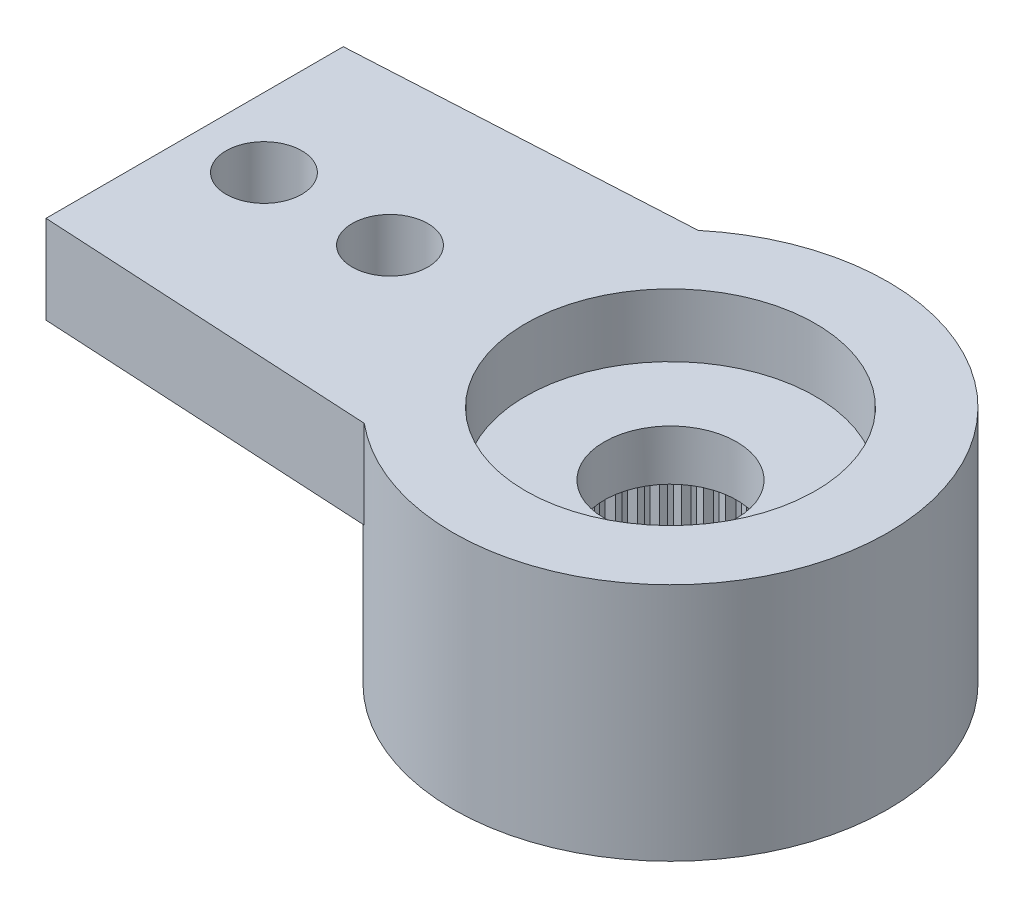
SolidWorks part; units mm, degrees
material "PVC Rígido"
ref_plane "Plano frontal" through (0, 0, 0) normal (0, 0, 1) x (1, 0, 0)
ref_plane "Plano superior" through (0, 0, 0) normal (0, 1, 0) x (1, 0, 0)
ref_plane "Plano direito" through (0, 0, 0) normal (1, 0, 0) x (0, 0, -1)
sketch "Esboço1" plane through (0, 0, 0) normal (0, 1, 0) x (1, 0, 0)
  line L0 (0, 0) -> (-14.05, 0) construction
  line L1 (-14.1591, 1.997) -> (-2.2091, 2.65)
  line L2 (-2.2091, -2.65) -> (-14.1591, -1.997)
  arc A0 (-2.2091, -2.65) -> (-2.2091, 2.65) centre (0, 0) ccw
  arc A1 (-14.1591, 1.997) -> (-14.1591, -1.997) centre (-14.05, 0) ccw
  dimension "D1" = 6.9
  dimension "D2" = 4
  dimension "D3" = 19.5
  dimension "D4" = 5.3
extrude "Ressalto-extrusão1" add sketch "Esboço1" against normal blind 1.4
sketch "Esboço2" plane through (0, -1.4, 0) normal (0, -1, 0) x (1, 0, 0)
  arc A0 (-2.2091, -2.65) -> (-2.2091, 2.65) centre (0, 0) ccw construction
  circle A1 centre (0, 0) radius 3.45
extrude "Ressalto-extrusão2" add sketch "Esboço2" along normal offset from surface (2.4 mm away) 3.8 up to face at (-7.242, 0, 0)
hole_wizard "Furo4" positions "Esboço9" profile "Esboço10" legacy end condition through all
sketch "Esboço9" plane through (0, 0, 0) normal (0, 1, 0) x (1, 0, 0)
  line L1 (-14.45, 0) -> (0, 0) construction
  arc A2 (-14.1591, 1.997) -> (-14.1591, -1.997) centre (-14.05, 0) ccw construction
  point P0 (-14.45, 0)
  point P19 (-16.05, 0)
  dimension "D1" = 1.6
sketch "Esboço10" plane through (-14.45, 0, 0) normal (1, 0, 0) x (0, 0, 1)
  line L0 (0, 0) -> (0, 3.8)
  line L1 (0, 3.8) -> (0.6, 3.8)
  line L2 (0.6, 3.8) -> (0.6, 0)
  line L3 (0.6, 0) -> (0, 0)
  line L4 (0, 110) -> (0, -10) construction
  dimension "Diameter" = 1.2
  dimension "Depth" = 3.8
pattern_linear "Padrão linear1" count 6 spacing 2 along (1, 0, 0) of "Furo4"
hole_wizard "Furo1" positions "Esboço3" profile "Esboço4" legacy
sketch "Esboço3" plane through (0, -3.8, 0) normal (0, -1, 0) x (-1, 0, 0)
  point P0 (0, 0)
sketch "Esboço4" plane through (0, -3.8, 0) normal (1, 0, 0) x (0, 0, -1)
  line L0 (0, 0) -> (0, 2)
  line L1 (0, 2) -> (2.475, 2)
  line L2 (2.475, 2) -> (2.475, 0)
  line L3 (2.475, 0) -> (0, 0)
  line L4 (0, 110) -> (0, -10) construction
  dimension "Diameter" = 4.95
  dimension "Depth" = 2
hole_wizard "Furo2" positions "Esboço5" profile "Esboço6" legacy
sketch "Esboço5" plane through (0, 0, 0) normal (0, 1, 0) x (1, 0, 0)
  point P0 (0, 0)
sketch "Esboço6" plane through (0, 0, 0) normal (1, 0, 0) x (0, 0, 1)
  line L0 (0, 0) -> (0, 1)
  line L1 (0, 1) -> (2.3, 1)
  line L2 (2.3, 1) -> (2.3, 0)
  line L3 (2.3, 0) -> (0, 0)
  line L4 (0, 110) -> (0, -10) construction
  dimension "Diameter" = 4.6
  dimension "Depth" = 1
hole_wizard "Furo3" positions "Esboço7" profile "Esboço8" legacy end condition through all
sketch "Esboço7" plane through (0, 0, 0) normal (0, 1, 0) x (1, 0, 0)
  point P0 (0, 0)
sketch "Esboço8" plane through (0, 0, 0) normal (1, 0, 0) x (0, 0, 1)
  line L0 (0, 0) -> (0, 3.8)
  line L1 (0, 3.8) -> (1.05, 3.8)
  line L2 (1.05, 3.8) -> (1.05, 0)
  line L3 (1.05, 0) -> (0, 0)
  line L4 (0, 110) -> (0, -10) construction
  dimension "Diameter" = 2.1
  dimension "Depth" = 3.8
sketch "Esboço11" plane through (0, -3.8, 0) normal (0, -1, 0) x (1, 0, 0)
  line L0 (-0.0981, 2.4731) -> (0, 2.375)
  line L1 (0, 2.375) -> (0.0981, 2.4731)
  line L2 (0, 0) -> (0, 2.475) construction
  circle A0 centre (0, 0) radius 2.375 construction
  circle A1 centre (0, 0) radius 2.475
  arc A2 (0.0981, 2.4731) -> (-0.0981, 2.4731) centre (0, 0) ccw
  dimension "D3" = 4.75
  dimension "D2" = 0.1
  dimension "D1" = 0
extrude "Ressalto-extrusão3" add sketch "Esboço11" against normal up to surface (2 mm away) up to face at (0, -1.8, 1.05)
pattern_circular "PadrãoCircular1" count 60 over 360 about axis through (0, 0, 0) along (0, 1, 0) of "Ressalto-extrusão3"
sketch "Sketch1" plane through (0, 0, 0) normal (0, 1, 0) x (1, 0, 0)
  line L1 (-24.55, 3.6347) -> (-7.55, 3.6347)
  line L2 (-24.55, 3.6347) -> (-24.55, -3.6347)
  line L3 (-24.55, -3.6347) -> (-7.55, -3.6347)
  line L4 (-7.55, 3.6347) -> (-7.55, -3.6347)
  line L5 (-24.55, 3.6347) -> (-7.55, -3.6347) construction
  line L6 (-24.55, -3.6347) -> (-7.55, 3.6347) construction
  arc A0 (-14.1591, 1.997) -> (-14.1591, -1.997) centre (-14.05, 0) ccw construction
  point P0 (-16.05, 0)
  dimension "D1" = 8.5
extrude "Cut-Extrude1" cut sketch "Sketch1" against normal blind 10
